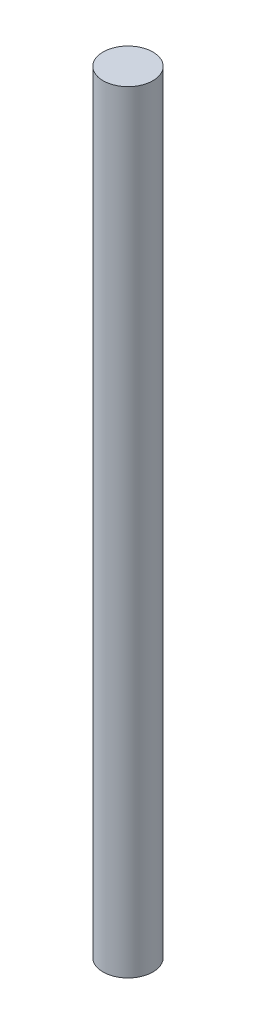
SolidWorks part; units mm, degrees
ref_plane "前视基准面" through (0, 0, 0) normal (0, 0, 1) x (1, 0, 0)
ref_plane "上视基准面" through (0, 0, 0) normal (0, 1, 0) x (1, 0, 0)
ref_plane "右视基准面" through (0, 0, 0) normal (1, 0, 0) x (0, 0, -1)
sketch "草图2" plane through (0, 0, 0) normal (0, 1, 0) x (1, 0, 0)
  circle A0 centre (0, 0) radius 2
extrude "凸台-拉伸1" add sketch "草图2" along normal blind 62
